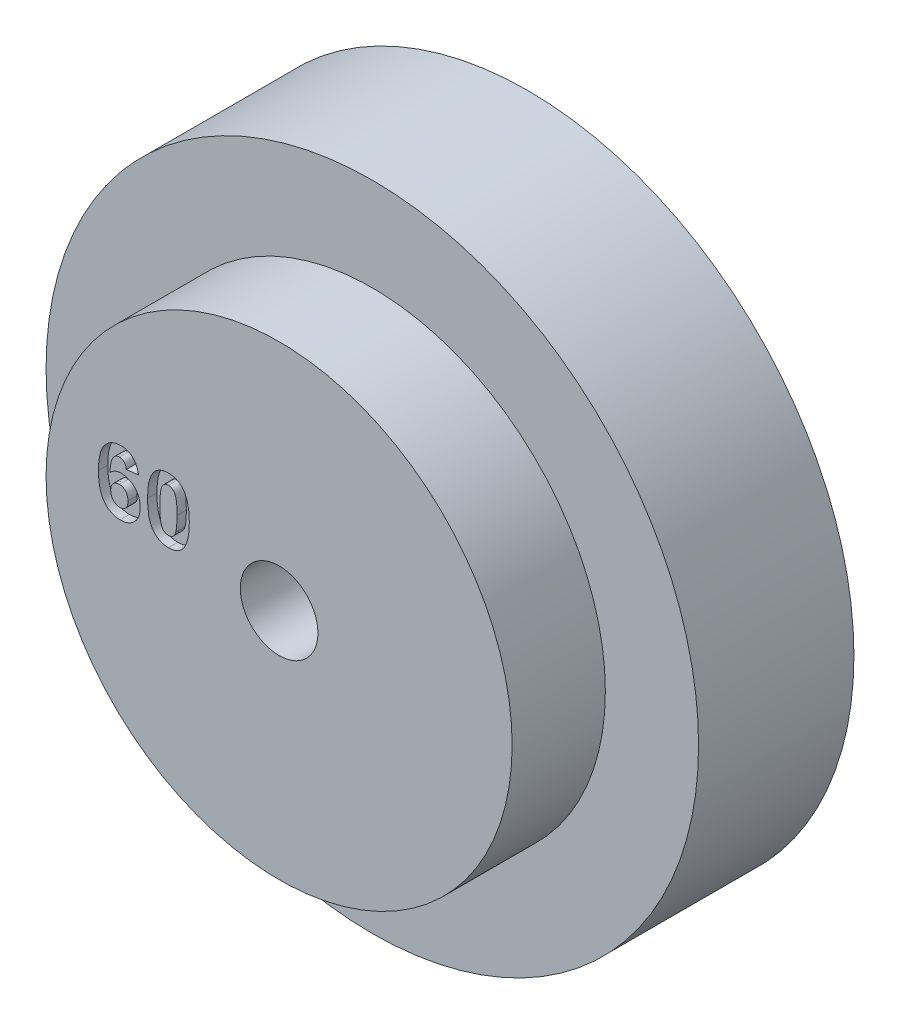
SolidWorks part; units mm, degrees
ref_plane "Front Plane" through (0, 0, 0) normal (0, 0, 1) x (1, 0, 0)
ref_plane "Top Plane" through (0, 0, 0) normal (0, 1, 0) x (1, 0, 0)
ref_plane "Right Plane" through (0, 0, 0) normal (1, 0, 0) x (0, 0, -1)
sketch "Sketch1" plane through (0, 0, 0) normal (0, 0, 1) x (1, 0, 0)
  circle A0 centre (0, 0) radius 21
  circle A1 centre (0, 0) radius 2.5
  dimension "D1" = 42
  dimension "D2" = 5
extrude "Boss-Extrude1" add sketch "Sketch1" along normal blind 10
sketch "Sketch2" plane through (0, 0, 10) normal (0, 0, 1) x (1, 0, 0)
  circle A0 centre (0, 0) radius 15
  circle A1 centre (0, 0) radius 2.5
  dimension "D1" = 30
extrude "Boss-Extrude2" add sketch "Sketch2" along normal blind 6
sketch "Sketch3" plane through (0, 0, 16) normal (0, 0, 1) x (1, 0, 0)
  line L0 (-15, 0) -> (15, 0) construction
  circle A0 centre (0, 0) radius 15 construction
  circle A1 centre (0, 0) radius 15 construction
  text T0 "  60" font "Arial" height in points 16
extrude "Cut-Extrude1" cut sketch "Sketch3" against normal blind 0.6
